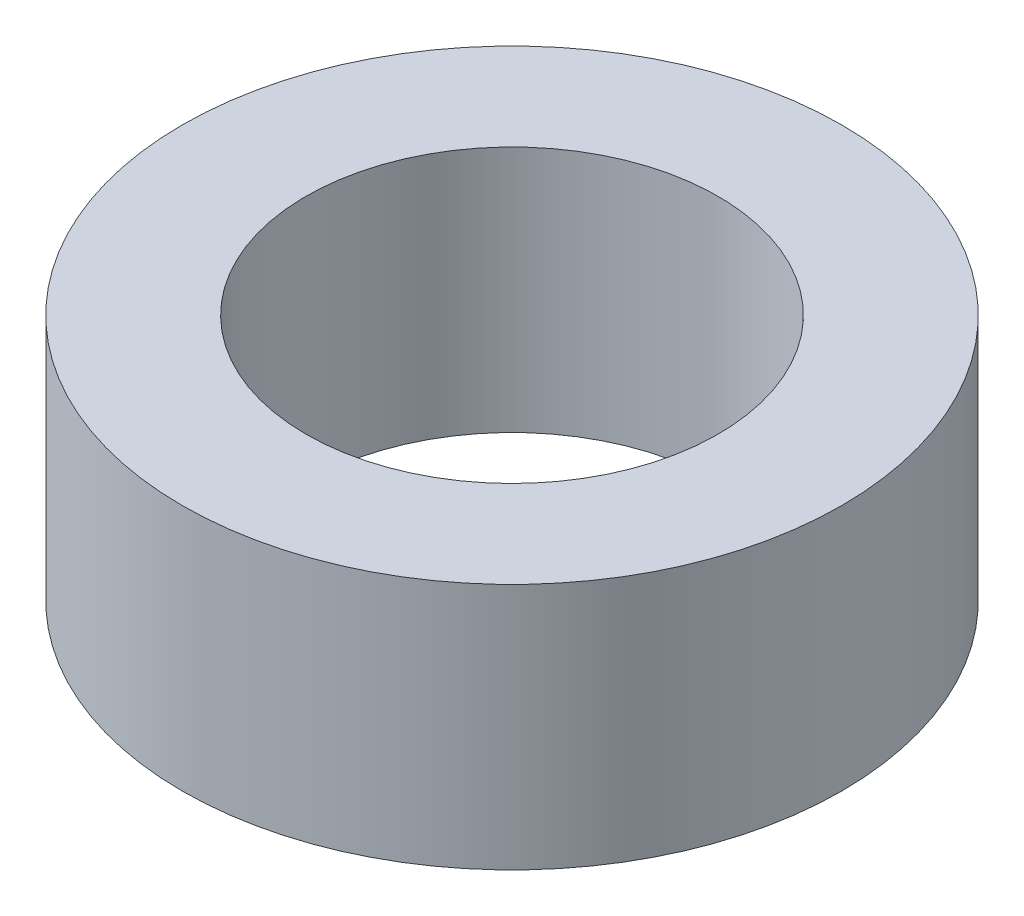
SolidWorks part; units mm, degrees
ref_plane "Front Plane" through (0, 0, 0) normal (0, 0, 1) x (1, 0, 0)
ref_plane "Top Plane" through (0, 0, 0) normal (0, 1, 0) x (1, 0, 0)
ref_plane "Right Plane" through (0, 0, 0) normal (1, 0, 0) x (0, 0, -1)
sketch "Sketch1" plane through (0, 0, 0) normal (0, 1, 0) x (1, 0, 0)
  circle A0 centre (0, 0) radius 8
  circle A1 centre (0, 0) radius 5
extrude "Boss-Extrude1" add sketch "Sketch1" along normal blind 6
